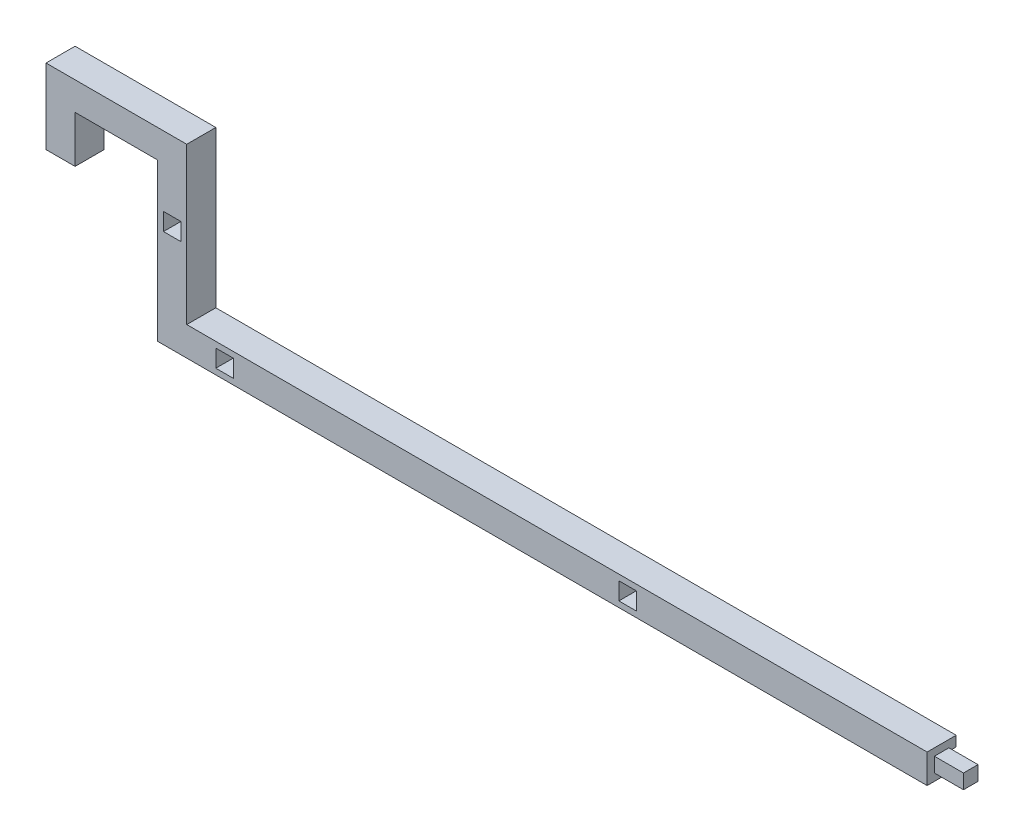
SolidWorks part; units mm, degrees
ref_plane "Front Plane" through (0, 0, 0) normal (0, 0, 1) x (1, 0, 0)
ref_plane "Top Plane" through (0, 0, 0) normal (0, 1, 0) x (1, 0, 0)
ref_plane "Right Plane" through (0, 0, 0) normal (1, 0, 0) x (0, 0, -1)
sketch "Sketch1" plane through (0, 0, 0) normal (0, 0, 1) x (1, 0, 0)
  line L0 (0, 6.7) -> (0, 8.05)
  line L5 (0, 0) -> (-5, 0)
  line L6 (-5, 0) -> (-5, 12.9)
  line L7 (-5, 12.9) -> (5.5, 12.9)
  line L8 (0, 8.05) -> (5.5, 8.05)
  line L10 (5.5, 12.9) -> (19.2, 12.9)
  line L11 (5.5, 8.05) -> (14.2, 8.05)
  line L16 (0, 6.7) -> (0, 0)
  line L17 (14.2, 8.05) -> (14.2, -18.95)
  line L18 (14.2, -18.95) -> (146.5, -18.95)
  line L19 (19.2, 12.9) -> (19.2, -13.95)
  line L20 (146.5, -18.95) -> (146.5, -13.95)
  line L21 (19.2, -13.95) -> (146.5, -13.95)
  dimension "D1" = 6.7
  dimension "D2" = 27
  dimension "D3" = 1.35
  dimension "D4" = 5
  dimension "D5" = 4.85
  dimension "D6" = 5
  dimension "D7" = 14.2
  dimension "D8" = 4.85
  dimension "D9" = 5
  dimension "D10" = 5
  dimension "D13" = 6.7
  dimension "D16" = 132.3
extrude "Boss-Extrude1" add sketch "Sketch1" along normal blind 5
sketch "Sketch2" plane through (146.5, 0, 0) normal (1, 0, 0) x (0, 0, -1)
  line L0 (-5, -18.95) -> (-5, -13.95) construction
  line L1 (-3.75, -17.7) -> (-1.25, -17.7)
  line L2 (-3.75, -17.7) -> (-3.75, -15.2)
  line L3 (-3.75, -15.2) -> (-1.25, -15.2)
  line L4 (-1.25, -17.7) -> (-1.25, -15.2)
  line L6 (-5, -13.95) -> (0, -13.95) construction
  point P4 (-3.75, -16.45)
  dimension "D1" = 2.5
  dimension "D2" = 2.5
  dimension "D3" = 1.25
  dimension "D4" = 1.25
extrude "Boss-Extrude2" add sketch "Sketch2" along normal blind 5
sketch "Sketch3" plane through (0, 0, 5) normal (0, 0, 1) x (1, 0, 0)
  line L0 (14.2, 8.05) -> (14.2, -18.95) construction
  line L1 (15.2, 0.9) -> (18.2, 0.9)
  line L2 (15.2, 0.9) -> (15.2, -2.1)
  line L3 (15.2, -2.1) -> (18.2, -2.1)
  line L4 (18.2, 0.9) -> (18.2, -2.1)
  line L5 (19.2, 12.9) -> (-5, 12.9) construction
  dimension "D1" = 3
  dimension "D2" = 3
  dimension "D3" = 1
  dimension "D4" = 12
extrude "Cut-Extrude1" cut sketch "Sketch3" against normal blind 10
sketch "Sketch5" plane through (0, 0, 0) normal (0, 0, -1) x (-1, 0, 0)
  line L0 (-146.5, -13.95) -> (-19.2, -13.95) construction
  line L1 (-27.2, -14.95) -> (-24.2, -14.95)
  line L2 (-27.2, -14.95) -> (-27.2, -17.95)
  line L3 (-27.2, -17.95) -> (-24.2, -17.95)
  line L4 (-24.2, -14.95) -> (-24.2, -17.95)
  line L5 (-96.5, -14.95) -> (-93.5, -14.95)
  line L6 (-96.5, -14.95) -> (-96.5, -17.95)
  line L7 (-96.5, -17.95) -> (-93.5, -17.95)
  line L8 (-93.5, -14.95) -> (-93.5, -17.95)
  line L9 (-14.2, 8.05) -> (-14.2, -18.95) construction
  line L10 (-146.5, -18.95) -> (-146.5, -13.95) construction
  dimension "D1" = 3
  dimension "D2" = 3
  dimension "D3" = 1
  dimension "D4" = 1
  dimension "D5" = 3
  dimension "D6" = 3
  dimension "D7" = 10
  dimension "D8" = 50
extrude "Cut-Extrude3" cut sketch "Sketch5" against normal blind 12
sketch "Sketch6" plane through (0, 0, 0) normal (0, 0, -1) x (-1, 0, 0)
  line L0 (-14.2, 8.05) -> (-14.2, -18.95) construction
  line L1 (-14.2, -17.2) -> (-146.5, -17.2)
  line L2 (-14.2, -17.2) -> (-14.2, -15.7)
  line L3 (-14.2, -15.7) -> (-146.5, -15.7)
  line L4 (-146.5, -17.2) -> (-146.5, -15.7)
  line L5 (-146.5, -17.7) -> (-146.5, -15.2) construction
  line L6 (-146.5, -13.95) -> (-19.2, -13.95) construction
  dimension "D1" = 1.5
  dimension "D2" = 1.75
extrude "Cut-Extrude4" cut sketch "Sketch6" against normal blind 2
